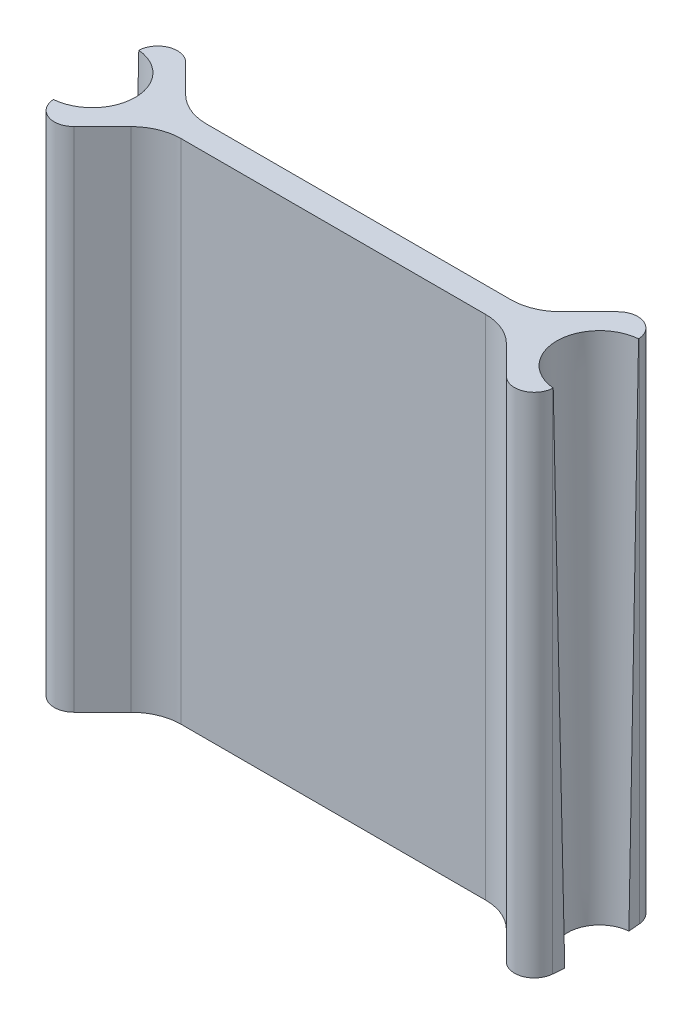
SolidWorks part; units mm, degrees
ref_plane "Front Plane" through (0, 0, 0) normal (0, 0, 1) x (1, 0, 0)
ref_plane "Top Plane" through (0, 0, 0) normal (0, 1, 0) x (1, 0, 0)
ref_plane "Right Plane" through (0, 0, 0) normal (1, 0, 0) x (0, 0, -1)
sketch "Sketch2" plane through (0, 0, 0) normal (0, 1, 0) x (1, 0, 0)
  line L0 (0, 0) -> (5, 0) construction
  line L1 (0, 0) -> (0.0553, 0.6326) construction
  line L2 (0.0553, 0.6326) -> (0.0751, 0.8586)
  line L3 (0.7385, 1.1) -> (1.2975, 0.541)
  line L4 (2, 0.25) -> (8, 0.25)
  line L5 (5, 0.25) -> (5, 0) construction
  line L6 (2, -0.25) -> (8, -0.25)
  line L7 (0.7385, -1.1) -> (1.2975, -0.541)
  line L8 (0.0553, -0.6326) -> (0.0751, -0.8586)
  line L9 (0.0553, 0.6326) -> (0.0553, -0.6326)
  line L10 (9.2615, -1.1) -> (8.7025, -0.541)
  line L11 (9.9447, -0.6326) -> (9.9249, -0.8586)
  line L12 (9.2615, 1.1) -> (8.7025, 0.541)
  line L13 (9.9447, 0.6326) -> (9.9249, 0.8586)
  line L14 (9.9447, 0.6326) -> (9.9447, -0.6326)
  line L15 (0, 0) -> (0.9192, -0.9192) construction
  circle A0 centre (0, 0) radius 0.635 construction
  circle A1 centre (10, 0) radius 0.635 construction
  arc A2 (0.0751, 0.8586) -> (0.7385, 1.1) centre (0.4631, 0.8246) cw
  arc A3 (1.2975, 0.541) -> (2, 0.25) centre (2, 1.2435) ccw
  arc A4 (1.2975, -0.541) -> (2, -0.25) centre (2, -1.2435) cw
  arc A5 (0.0751, -0.8586) -> (0.7385, -1.1) centre (0.4631, -0.8246) ccw
  arc A6 (8.7025, -0.541) -> (8, -0.25) centre (8, -1.2435) ccw
  arc A7 (8.7025, 0.541) -> (8, 0.25) centre (8, 1.2435) cw
  arc A8 (9.9249, -0.8586) -> (9.2615, -1.1) centre (9.5369, -0.8246) cw
  arc A10 (9.9249, 0.8586) -> (9.2615, 1.1) centre (9.5369, 0.8246) ccw
  point P27 (5, -0.25)
  dimension "D1" = 1.27
  dimension "D7" = 1.1
  dimension "D5" = 1.3
  dimension "D2" = 5
  dimension "D3" = 95
  dimension "D4" = 0.25
  dimension "D6" = 135
  dimension "D8" = 3
  dimension "D9" = 0.8246
extrude "Boss-Extrude2" add sketch "Sketch2" along normal blind 10
sketch "Sketch5" plane through (0, 0, 0) normal (0, -1, 0) x (1, 0, 0)
  circle A0 centre (0, 0) radius 0.635
  circle A1 centre (0, 0) radius 0.635 construction
  circle A2 centre (10, 0) radius 0.635
  circle A3 centre (10, 0) radius 0.635 construction
extrude "Cut-Extrude1" cut sketch "Sketch5" against normal up to next (10 mm away) draft 1.2 draft outward yes
